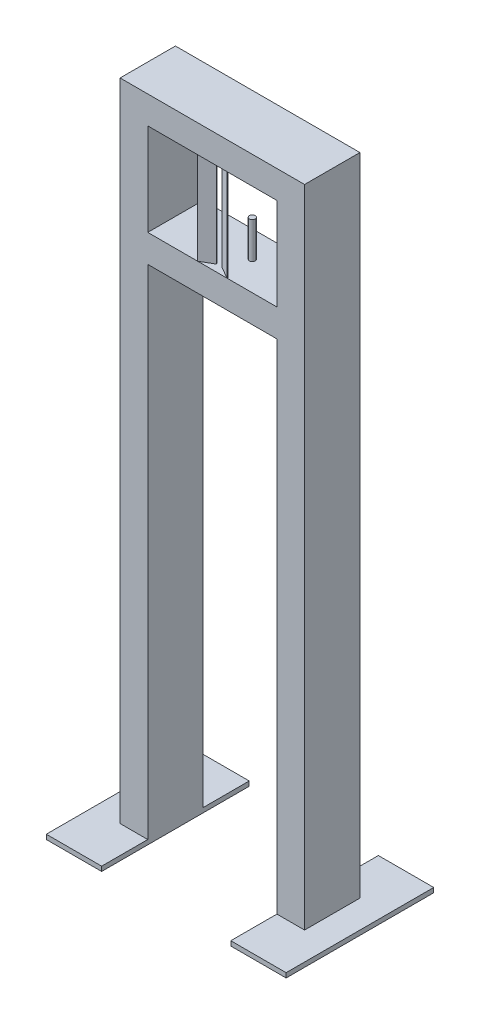
SolidWorks part; units mm, degrees
ref_plane "Front Plane" through (0, 0, 0) normal (0, 0, 1) x (1, 0, 0)
ref_plane "Top Plane" through (0, 0, 0) normal (0, 1, 0) x (1, 0, 0)
ref_plane "Right Plane" through (0, 0, 0) normal (1, 0, 0) x (0, 0, -1)
sketch "Sketch1" plane through (0, 0, 0) normal (0, 1, 0) x (1, 0, 0)
  line L0 (0, 0) -> (0, -375.7127) construction
  line L1 (165.1, 0) -> (165.1, -203.2)
  line L2 (-88.9, 0) -> (-165.1, 0)
  line L3 (-88.9, 0) -> (-88.9, -203.2)
  line L4 (-88.9, -203.2) -> (-165.1, -203.2)
  line L5 (-165.1, 0) -> (-165.1, -203.2)
  line L6 (88.9, -203.2) -> (165.1, -203.2)
  line L7 (88.9, 0) -> (165.1, 0)
  line L8 (88.9, 0) -> (88.9, -203.2)
  dimension "D1" = 203.2
  dimension "D2" = 76.2
  dimension "D3" = 177.8
extrude "Boss-Extrude1" add sketch "Sketch1" along normal blind 6.35
sketch "Sketch2" plane through (0, 6.35, 0) normal (0, 1, 0) x (1, 0, 0)
  line L0 (-165.1, -101.6) -> (165.1, -101.6) construction
  line L1 (-165.1, 0) -> (-165.1, -203.2) construction
  line L2 (165.1, -203.2) -> (165.1, 0) construction
  line L3 (0, -57.8044) -> (0, -151.3067) construction
  line L4 (-88.9, -203.2) -> (-88.9, 0) construction
  line L5 (-127, -139.7) -> (-88.9, -139.7)
  line L6 (-127, -139.7) -> (-127, -63.5)
  line L7 (-127, -63.5) -> (-88.9, -63.5)
  line L8 (-88.9, -139.7) -> (-88.9, -63.5)
  line L9 (-127, -139.7) -> (-88.9, -63.5) construction
  line L10 (-127, -63.5) -> (-88.9, -139.7) construction
  line L11 (127, -139.7) -> (127, -63.5)
  line L12 (127, -139.7) -> (88.9, -139.7)
  line L13 (88.9, -139.7) -> (88.9, -63.5)
  line L14 (127, -63.5) -> (88.9, -63.5)
  point P9 (-107.95, -101.6)
  dimension "D1" = 76.2
  dimension "D2" = 38.1
extrude "Boss-Extrude2" add sketch "Sketch2" along normal blind 889
sketch "Sketch3" plane through (0, 0, 139.7) normal (0, 0, 1) x (1, 0, 0)
  line L0 (88.9, 895.35) -> (88.9, 6.35) construction
  line L1 (-88.9, 895.35) -> (88.9, 895.35)
  line L2 (-88.9, 895.35) -> (-88.9, 857.25)
  line L3 (-88.9, 857.25) -> (88.9, 857.25)
  line L4 (88.9, 895.35) -> (88.9, 857.25)
  line L5 (-88.9, 895.35) -> (-88.9, 6.35) construction
  line L6 (88.9, 730.25) -> (-88.9, 730.25)
  line L7 (88.9, 730.25) -> (88.9, 692.15)
  line L8 (88.9, 692.15) -> (-88.9, 692.15)
  line L9 (-88.9, 730.25) -> (-88.9, 692.15)
  dimension "D1" = 38.1
  dimension "D2" = 38.1
  dimension "D3" = 203.2
extrude "Boss-Extrude3" add sketch "Sketch3" against normal up to surface (76.2 mm away) up to face at (-107.95, 450.85, 63.5)
sketch "Sketch6" plane through (0, 730.25, 0) normal (0, 1, 0) x (1, 0, 0)
  line L0 (0, -139.7) -> (0, -63.5) construction
  line L1 (88.9, -139.7) -> (-88.9, -139.7) construction
  line L2 (-88.9, -63.5) -> (88.9, -63.5) construction
  line L3 (-3.75, -130.2) -> (-20.2045, -139.7)
  line L4 (-4.375, -129.1175) -> (-20.8295, -138.6175)
  line L5 (-20.8295, -138.6175) -> (-20.2045, -139.7)
  line L6 (-3.75, -130.2) -> (-4.375, -129.1175)
  line L7 (20.8295, -138.6175) -> (20.2045, -139.7)
  line L8 (4.375, -129.1175) -> (20.8295, -138.6175)
  line L9 (3.75, -130.2) -> (4.375, -129.1175)
  line L10 (3.75, -130.2) -> (20.2045, -139.7)
  dimension "D1" = 30
  dimension "D2" = 19
  dimension "D3" = 7.5
  dimension "D4" = 1.25
extrude "Boss-Extrude4" add sketch "Sketch6" along normal up to next
sketch "Sketch7" plane through (0, 730.25, 0) normal (0, 1, 0) x (1, 0, 0)
  line L0 (0, -139.7) -> (0, -63.5) construction
  line L1 (20.2045, -139.7) -> (-20.2045, -139.7) construction
  line L2 (-88.9, -63.5) -> (88.9, -63.5) construction
  line L3 (-56.3342, -99.7) -> (54.7215, -99.7) construction
  line L4 (88.9, -139.7) -> (20.2045, -139.7) construction
  circle A0 centre (15, -99.7) radius 4
  dimension "D2" = 8
  dimension "D3" = 15
  dimension "D1" = 40
extrude "Boss-Extrude5" add sketch "Sketch7" along normal blind 50
